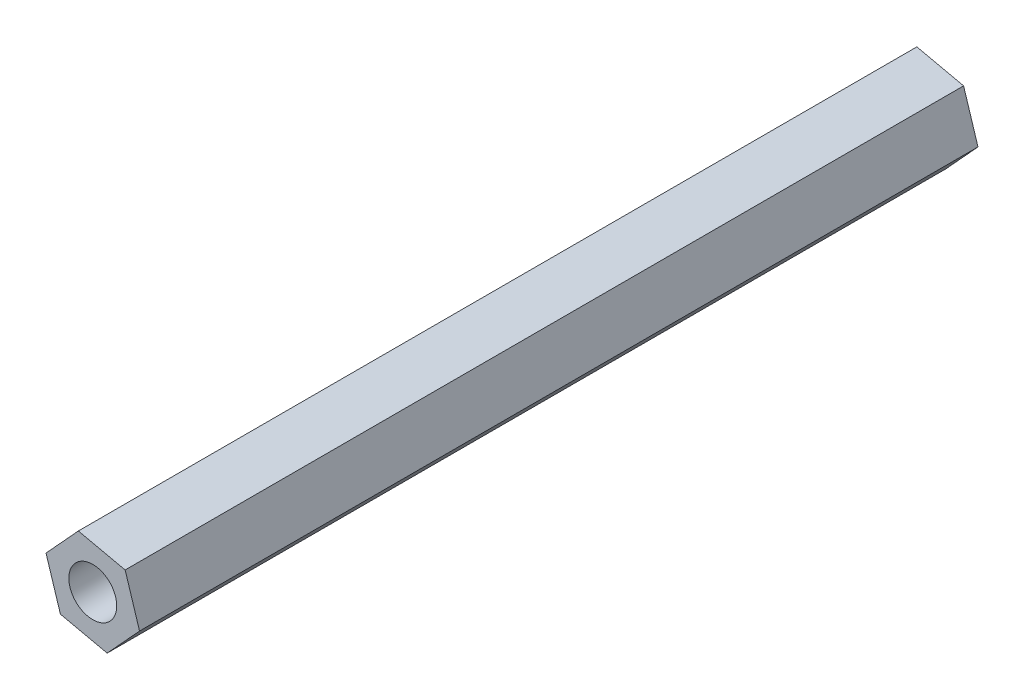
SolidWorks part; units mm, degrees
ref_plane "前视基准面" through (0, 0, 0) normal (0, 0, 1) x (1, 0, 0)
ref_plane "上视基准面" through (0, 0, 0) normal (0, 1, 0) x (1, 0, 0)
ref_plane "右视基准面" through (0, 0, 0) normal (1, 0, 0) x (0, 0, -1)
sketch "草图1" plane through (0, 0, 0) normal (0, 0, 1) x (1, 0, 0)
  line L1 (-154.2026, 46.0799) -> (-156.9051, 43.131)
  line L2 (-156.9051, 43.131) -> (-155.7025, 39.3161)
  line L3 (-155.7025, 39.3161) -> (-151.7974, 38.4501)
  line L4 (-151.7974, 38.4501) -> (-149.0949, 41.399)
  line L5 (-149.0949, 41.399) -> (-150.2975, 45.2139)
  line L6 (-150.2975, 45.2139) -> (-154.2026, 46.0799)
  circle A0 centre (-153, 42.265) radius 3.4641 construction
  circle A1 centre (-153, 42.265) radius 2
  dimension "D1" = 4
  dimension "D2" = 4
extrude "凸台-拉伸1" add sketch "草图1" along normal blind 70
